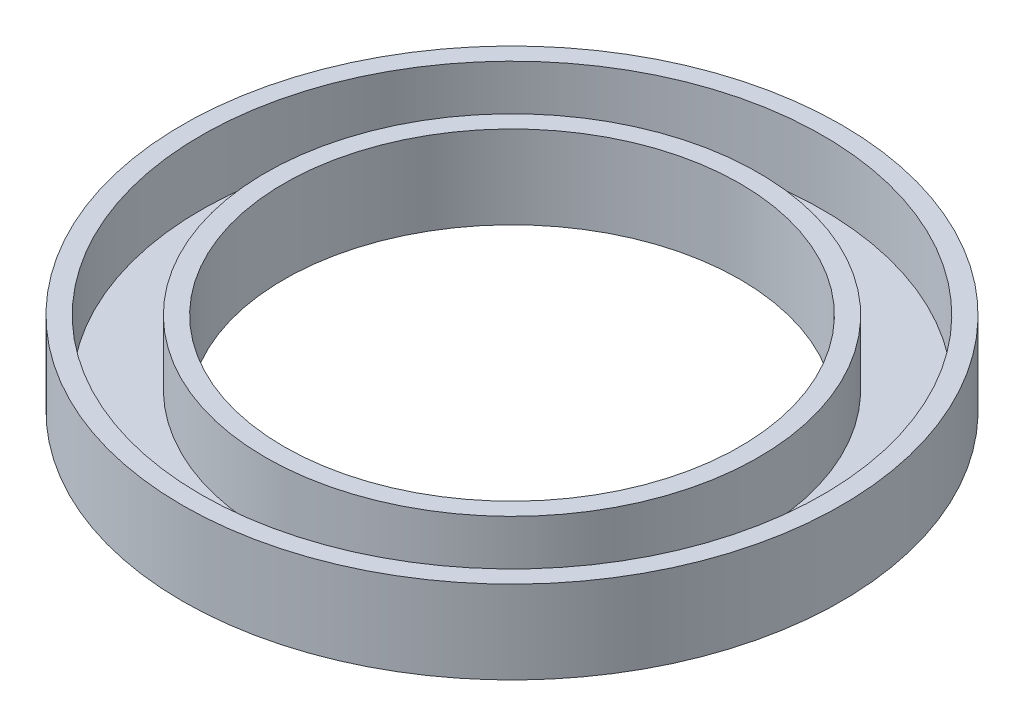
SolidWorks part; units mm, degrees
ref_plane "前视基准面" through (0, 0, 0) normal (0, 0, 1) x (1, 0, 0)
ref_plane "上视基准面" through (0, 0, 0) normal (0, 1, 0) x (1, 0, 0)
ref_plane "右视基准面" through (0, 0, 0) normal (1, 0, 0) x (0, 0, -1)
other "Configuration Table"
sketch "草图1" plane through (0, 0, 0) normal (0, 0, 1) x (1, 0, 0)
  line L0 (0, 46.7269) -> (0, -44.9569) construction
  line L1 (19.9, 17.2772) -> (19.9, 12.0772)
  line L2 (19.9, 12.0772) -> (25.1, 12.0772)
  line L3 (25.1, 12.0772) -> (25.1, 17.2772)
  line L4 (18.4, 17.2772) -> (18.4, 10.5772)
  line L5 (18.4, 10.5772) -> (26.6, 10.5772)
  line L6 (26.6, 10.5772) -> (26.6, 17.2772)
  line L7 (18.4, 17.2772) -> (19.9, 17.2772)
  line L8 (25.1, 17.2772) -> (26.6, 17.2772)
  dimension "D1" = 39.8
  dimension "D2" = 50.2
  dimension "D3" = 5.2
  dimension "D4" = 5.2
  dimension "D5" = 1.5
revolve "旋转1" add sketch "草图1" angle 360 about L0
